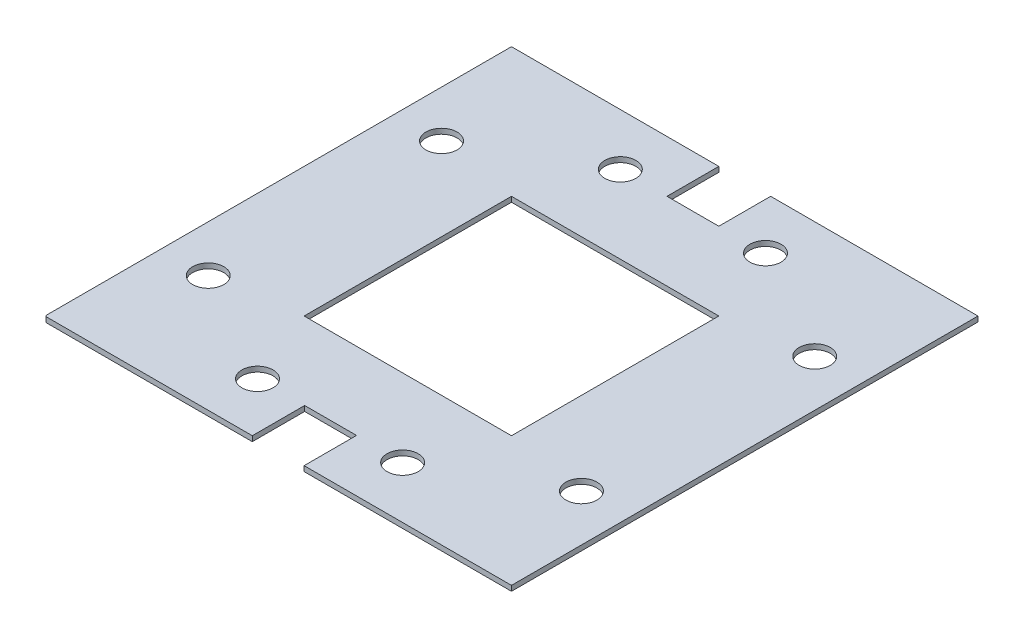
SolidWorks part; units mm, degrees
ref_plane "Alzado" through (0, 0, 0) normal (0, 0, 1) x (1, 0, 0)
ref_plane "Planta" through (0, 0, 0) normal (0, 1, 0) x (1, 0, 0)
ref_plane "Vista lateral" through (0, 0, 0) normal (1, 0, 0) x (0, 0, -1)
sketch "Croquis1" plane through (0, 0, 0) normal (0, 1, 0) x (1, 0, 0)
  line L0 (0, 0) -> (20, 20) construction
  line L1 (0, 0) -> (20, 0)
  line L2 (0, 0) -> (0, 20)
  line L3 (0, 20) -> (20, 20)
  line L4 (20, 0) -> (20, 20)
  line L5 (-12.5, -12.5) -> (32.5, -12.5)
  line L6 (-12.5, -12.5) -> (-12.5, 32.5)
  line L7 (-12.5, 32.5) -> (32.5, 32.5)
  line L8 (32.5, -12.5) -> (32.5, 32.5)
  line L9 (-12.5, 32.5) -> (32.5, -12.5) construction
  line L10 (-14.9749, 34.9749) -> (-12.5, 32.5) construction
  line L11 (28, 10) -> (32.5, 10) construction
  line L12 (10, 10) -> (10, -17.4738) construction
  line L13 (10, 10) -> (0, 10) construction
  line L14 (10, 25) -> (10, 32.5) construction
  line L15 (-5, 25) -> (25, 25) construction
  line L16 (-5, 25) -> (-5, -5) construction
  line L17 (-5, -5) -> (25, -5) construction
  line L18 (25, 25) -> (25, -5) construction
  line L19 (-5, 25) -> (25, -5) construction
  line L20 (-5, -5) -> (25, 25) construction
  line L21 (28, -1.25) -> (28, 10) construction
  line L22 (28, 10) -> (28, 21.25) construction
  line L23 (3, 27.5) -> (10, 27.5) construction
  line L24 (10, 27.5) -> (17, 27.5) construction
  circle A4 centre (-8, 21.25) radius 1.5
  circle A5 centre (-8, -1.25) radius 1.5
  circle A9 centre (3, 27.5) radius 1.5
  circle A10 centre (17, 27.5) radius 1.5
  arc A12 (-12.5, -12.3985) -> (-12.3985, -12.5) centre (-9.9749, -9.9749) ccw
  circle A13 centre (17, -7.5) radius 1.5
  circle A17 centre (3, -7.5) radius 1.5
  circle A23 centre (28, 21.25) radius 1.5
  circle A24 centre (28, -1.25) radius 1.5
  point P9 (10, 10)
  point P10 (10, 10)
  dimension "D3" = 18
  dimension "D4" = 3
  dimension "D9" = 3
  dimension "D1" = 20
  dimension "D2" = 45
  dimension "D5" = 3.5
  dimension "D6" = 7
  dimension "D8" = 30
  dimension "D10" = 11.25
  dimension "D7" = 17.5
extrude "Saliente-Extruir1" add sketch "Croquis1" along normal blind 0.5
sketch "Croquis3" plane through (0, 0.5, 0) normal (0, 1, 0) x (1, 0, 0)
  line L0 (-12.5, 32.5) -> (32.5, 32.5) construction
  line L1 (7.5, 32.5) -> (12.5, 32.5)
  line L2 (7.5, 32.5) -> (7.5, 27.5)
  line L3 (7.5, 27.5) -> (12.5, 27.5)
  line L4 (12.5, 32.5) -> (12.5, 27.5)
  line L5 (-12.3985, -12.5) -> (32.5, -12.5) construction
  line L6 (7.5, -12.5) -> (12.5, -12.5)
  line L7 (7.5, -12.5) -> (7.5, -7.4492)
  line L8 (7.5, -7.4492) -> (12.5, -7.4492)
  line L9 (12.5, -12.5) -> (12.5, -7.4492)
  line L10 (-12.5, 10.0508) -> (32.5, 10) construction
  line L11 (-12.5, -12.3985) -> (-12.5, 32.5) construction
  line L12 (32.5, -12.5) -> (32.5, 32.5) construction
  line L13 (10, -7.4492) -> (10, 10.0254) construction
  line L14 (10, 10.0254) -> (10, 27.5) construction
  dimension "D1" = 5
  dimension "D2" = 5
extrude "Cortar-Extruir2" cut sketch "Croquis3" against normal blind 10
